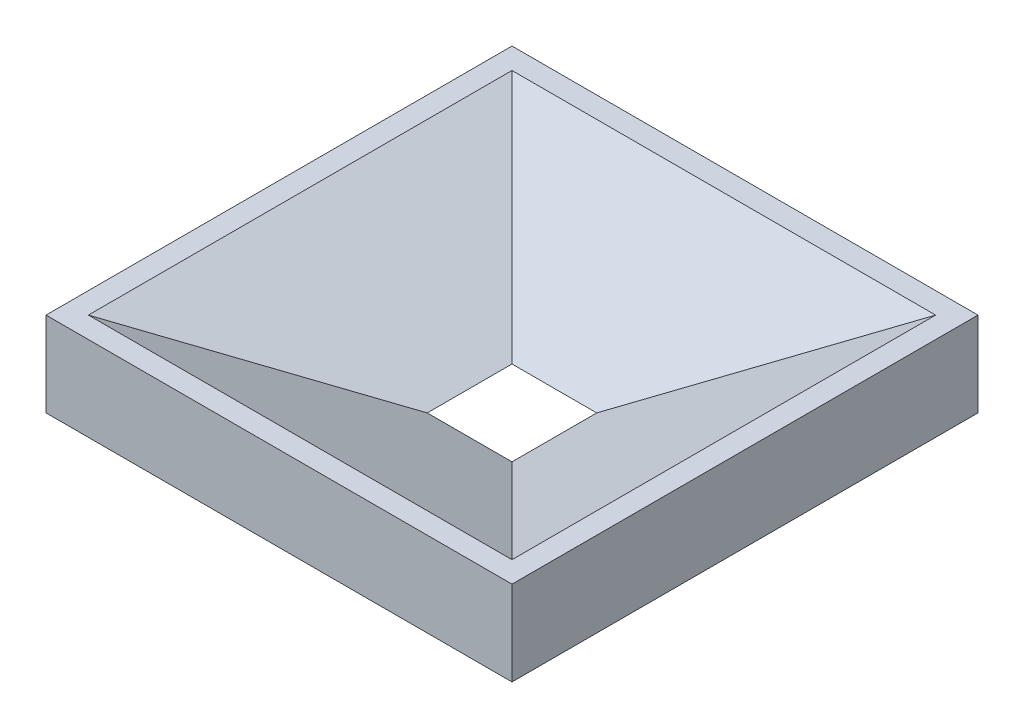
SolidWorks part; units mm, degrees
ref_plane "Alzado" through (0, 0, 0) normal (0, 0, 1) x (1, 0, 0)
ref_plane "Planta" through (0, 0, 0) normal (0, 1, 0) x (1, 0, 0)
ref_plane "Vista lateral" through (0, 0, 0) normal (1, 0, 0) x (0, 0, -1)
sketch "Croquis1" plane through (0, 0, 0) normal (0, 1, 0) x (1, 0, 0)
  line L0 (0, 0) -> (110, 110) construction
  line L1 (0, 0) -> (110, 0)
  line L2 (0, 0) -> (0, 110)
  line L3 (0, 110) -> (110, 110)
  line L4 (110, 0) -> (110, 110)
  line L6 (5, 5) -> (105, 5)
  line L7 (5, 5) -> (5, 105)
  line L8 (5, 105) -> (105, 105)
  line L9 (105, 5) -> (105, 105)
  line L10 (5, 5) -> (105, 105) construction
  line L11 (5, 105) -> (105, 5) construction
  point P4 (55, 55)
  dimension "D1" = 110
  dimension "D2" = 100
extrude "Saliente-Extruir1" add sketch "Croquis1" along normal blind 20
sketch "Croquis2" plane through (0, 0, -105) normal (0, 0, 1) x (1, 0, 0)
  line L0 (5, 20) -> (45, 0)
  line L1 (0, 0) -> (110, 0) construction
  line L2 (45, 0) -> (5, 0)
  line L3 (5, 0) -> (5, 20)
  line L4 (55, 0) -> (55, 20) construction
  line L5 (0, 20) -> (110, 20) construction
  line L6 (105, 0) -> (105, 20)
  line L7 (65, 0) -> (105, 0)
  line L8 (105, 20) -> (65, 0)
  point P5 (55, 0)
  dimension "D1" = 10
extrude "Saliente-Extruir2" add sketch "Croquis2" along normal up to surface (100 mm away) up to face at (55, 10, -5)
ref_plane "Plano1" through (55, 0, 0) normal (1, 0, 0) x (0, 0, -1)
sketch "Croquis3" plane through (55, 0, 0) normal (1, 0, 0) x (0, 0, -1)
  line L0 (5, 20) -> (45, 0)
  line L1 (0, 0) -> (110, 0) construction
  line L2 (5, 20) -> (5, 0)
  line L3 (5, 0) -> (45, 0)
  line L4 (55, 0) -> (55, 20) construction
  line L5 (0, 20) -> (110, 20) construction
  line L6 (105, 0) -> (65, 0)
  line L7 (105, 20) -> (105, 0)
  line L8 (105, 20) -> (65, 0)
  point P5 (55, 0)
  dimension "D1" = 10
extrude "Saliente-Extruir3" add sketch "Croquis3" along normal up to surface and the other way up to surface up to face at (110, 10, -55) other way up to face at (0, 10, -55)
